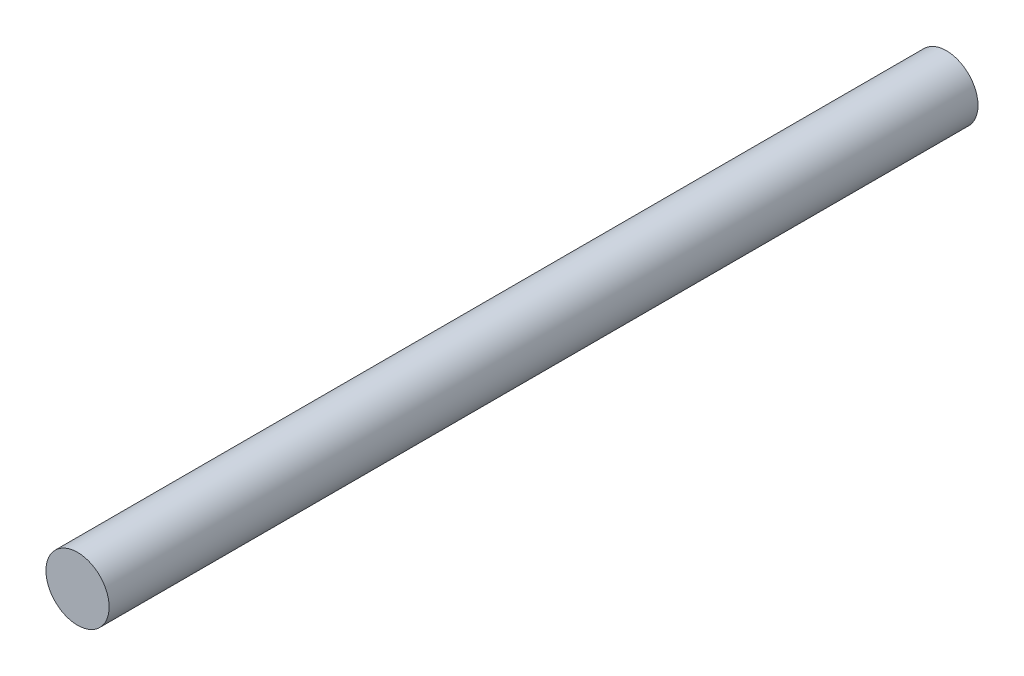
SolidWorks part; units mm, degrees
ref_plane "Plan de face" through (0, 0, 0) normal (0, 0, 1) x (1, 0, 0)
ref_plane "Plan de dessus" through (0, 0, 0) normal (0, 1, 0) x (1, 0, 0)
ref_plane "Plan de droite" through (0, 0, 0) normal (1, 0, 0) x (0, 0, -1)
sketch "Esquisse1" plane through (0, 0, 0) normal (0, 0, 1) x (1, 0, 0)
  circle A0 centre (0, 0) radius 10
  dimension "D1" = 20
extrude "Boss.-Extru.1" add sketch "Esquisse1" along normal mid plane 275
